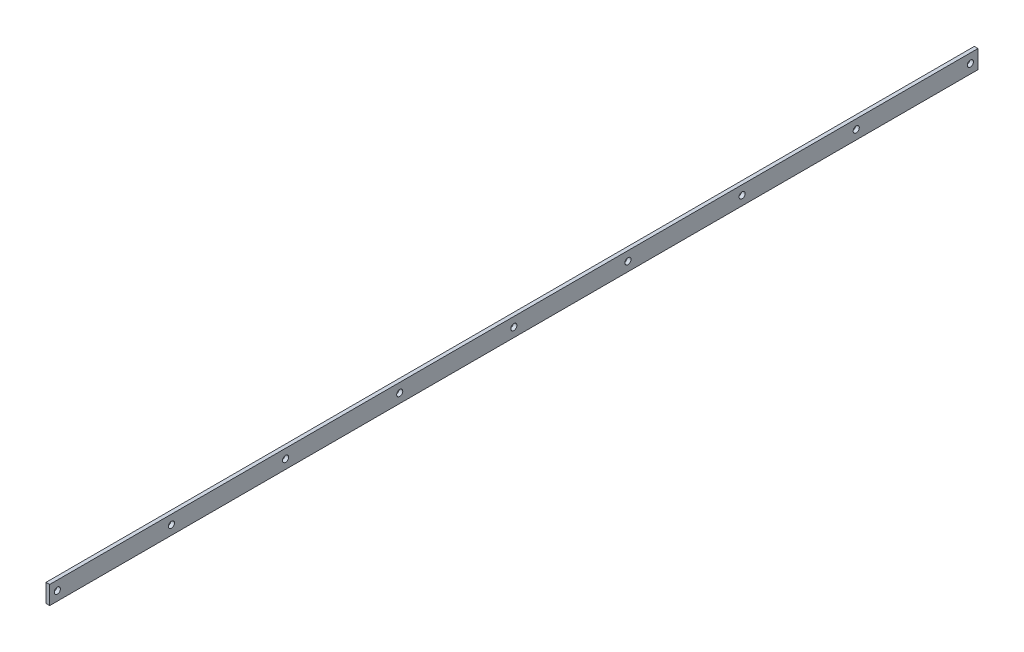
SolidWorks part; units mm, degrees
material "ASTM A36 Steel"
ref_plane "Front Plane" through (0, 0, 0) normal (0, 0, 1) x (1, 0, 0)
ref_plane "Top Plane" through (0, 0, 0) normal (0, 1, 0) x (1, 0, 0)
ref_plane "Right Plane" through (0, 0, 0) normal (1, 0, 0) x (0, 0, -1)
sketch "Sketch1" plane through (0, 0, 0) normal (1, 0, 0) x (0, 0, -1)
  line L1 (-1517, -30) -> (1517, -30)
  line L2 (-1517, -30) -> (-1517, 30)
  line L3 (-1517, 30) -> (1517, 30)
  line L4 (1517, -30) -> (1517, 30)
  line L5 (-1517, -30) -> (1517, 30) construction
  line L6 (-1517, 30) -> (1517, -30) construction
  point P0 (0, 0)
  dimension "D1" = 60
  dimension "D2" = 3034
extrude "Boss-Extrude1" add sketch "Sketch1" along normal blind 12
sketch "Sketch2" plane through (12, 0, 0) normal (1, 0, 0) x (0, 0, -1)
  line L0 (-1517, 30) -> (-1517, -30) construction
  circle A0 centre (-1492, 0) radius 10
  dimension "D1" = 20
  dimension "D2" = 25
extrude "Cut-Extrude1" cut sketch "Sketch2" against normal blind 12
pattern_linear "LPattern1" count 9 spacing 373 along (0, 0, -1) of "Cut-Extrude1"
